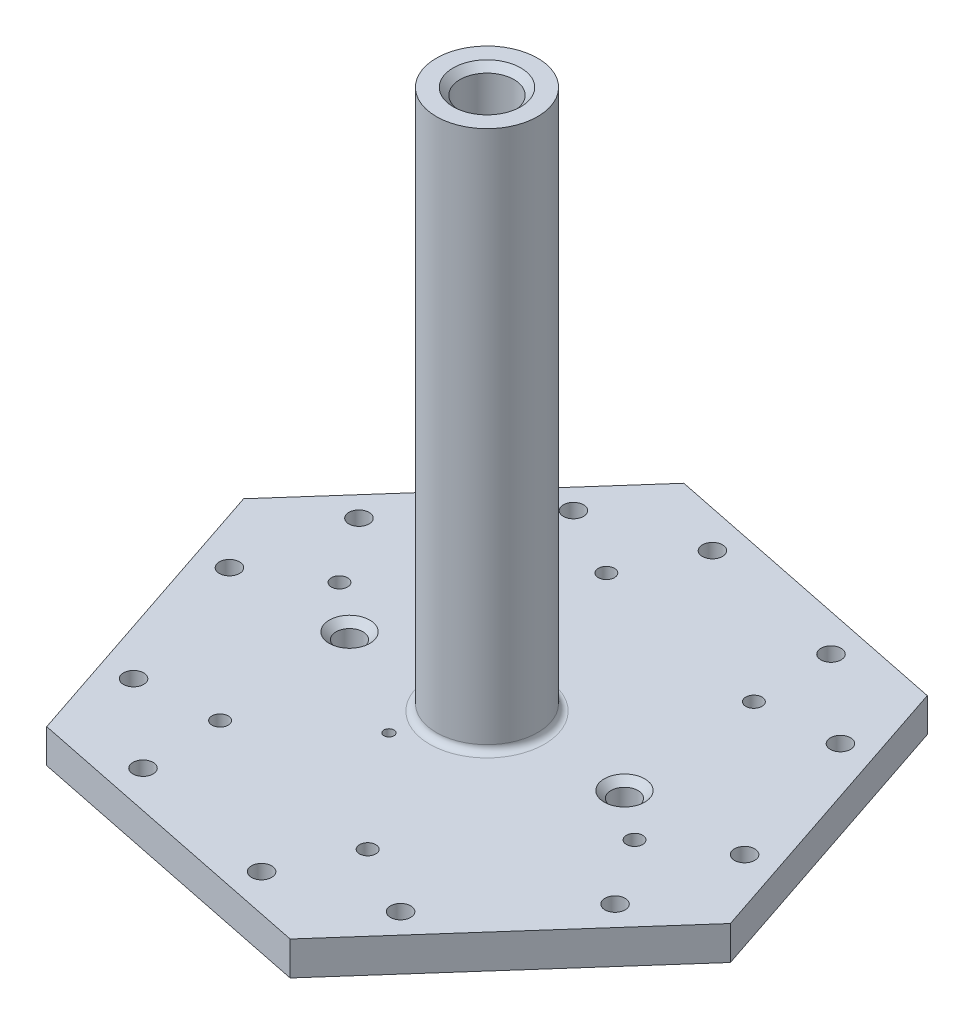
SolidWorks part; units mm, degrees
ref_plane "Front" through (0, 0, 0) normal (0, 0, 1) x (1, 0, 0)
ref_plane "Top" through (0, 0, 0) normal (0, 1, 0) x (1, 0, 0)
ref_plane "Right" through (0, 0, 0) normal (1, 0, 0) x (0, 0, -1)
sketch "Sketch1" plane through (0, 0, 0) normal (0, 1, 0) x (1, 0, 0)
  line L1 (18.6052, -55.63) -> (57.4796, -11.7025)
  line L2 (57.4796, -11.7025) -> (38.8744, 43.9276)
  line L3 (38.8744, 43.9276) -> (-18.6052, 55.63)
  line L4 (-18.6052, 55.63) -> (-57.4796, 11.7025)
  line L5 (-57.4796, 11.7025) -> (-38.8744, -43.9276)
  line L6 (-38.8744, -43.9276) -> (18.6052, -55.63)
  circle A0 centre (0, 0) radius 50.8 construction
  dimension "D1" = 101.6
extrude "Boss-Extrude1" add sketch "Sketch1" along normal blind 6.35
sketch "Sketch2" plane through (0, 6.35, 0) normal (0, 1, 0) x (1, 0, 0)
  circle A0 centre (0, 0) radius 9.525
  dimension "D1" = 19.05
extrude "Boss-Extrude2" add sketch "Sketch2" along normal blind 101.6
fillet "Fillet1" radius 1.27 1 edges at (0, 6.35, 9.525)
sketch "Sketch3" plane through (0, 107.95, 0) normal (0, 1, 0) x (1, 0, 0)
  circle A0 centre (0, 0) radius 5.08
  dimension "D1" = 10.16
extrude "Cut-Extrude1" cut sketch "Sketch3" against normal blind 8.89
chamfer "Chamfer1" distance 1.27 angle 45 1 edges at (0, 107.95, 5.08)
sketch "Sketch9" plane through (0, 6.35, 0) normal (0, 1, 0) x (1, 0, 0)
  circle A0 centre (-5.6821, -12.7622) radius 0.9525
sketch "Sketch10" plane through (0, 6.35, 0) normal (0, 1, 0) x (1, 0, 0)
  line L0 (-25.855, 0) -> (25.855, 0) construction
  circle A0 centre (-25.855, 0) radius 2.54
  circle A1 centre (25.855, 0) radius 2.54
  dimension "D1" = 5.08
extrude "Cut-Extrude2" cut sketch "Sketch9" against normal through all
extrude "Cut-Extrude3" cut sketch "Sketch10" against normal through all
chamfer "Chamfer2" distance 1.27 angle 45 2 edges at (-25.855, 6.35, 2.54) (25.855, 6.35, 2.54)
sketch "Sketch11" plane through (0, 0, 0) normal (0, -1, 0) x (1, 0, 0)
  line L0 (0, 0) -> (18.6052, 55.63) construction
  circle A0 centre (11.2788, 33.7239) radius 1.524
  circle A1 centre (34.8452, 7.0942) radius 1.524
  circle A2 centre (23.5664, -26.6297) radius 1.524
  circle A3 centre (-11.2788, -33.7239) radius 1.524
  circle A4 centre (-34.8452, -7.0942) radius 1.524
  circle A5 centre (-23.5664, 26.6297) radius 1.524
  point P18 (0, 0)
  dimension "D1" = 3.048
  dimension "D2" = 35.56
  dimension "D3" = 6
extrude "Cut-Extrude4" cut sketch "Sketch11" against normal through all
sketch "Sketch12" plane through (0, 6.35, 0) normal (0, 1, 0) x (1, 0, 0)
  circle A0 centre (-47.5899, -0.8508) radius 1.8986
  circle A1 centre (-38.5266, -27.9504) radius 1.8986
  circle A2 centre (-43.469, 19.3898) radius 1.8986
  circle A3 centre (-24.5317, 40.7886) radius 1.8986
  circle A4 centre (-4.9425, 47.3402) radius 1.8987
  circle A5 centre (23.0581, 41.6394) radius 1.8986
  circle A6 centre (38.5266, 27.9504) radius 1.8986
  circle A7 centre (47.5899, 0.8508) radius 1.8987
  circle A8 centre (43.469, -19.3898) radius 1.8987
  circle A9 centre (24.5317, -40.7886) radius 1.8986
  circle A10 centre (4.9425, -47.3402) radius 1.8987
  circle A11 centre (-23.0581, -41.6394) radius 1.8986
  point P29 (0, 0)
  dimension "D1" = 6
extrude "Cut-Extrude5" cut sketch "Sketch12" against normal through all
